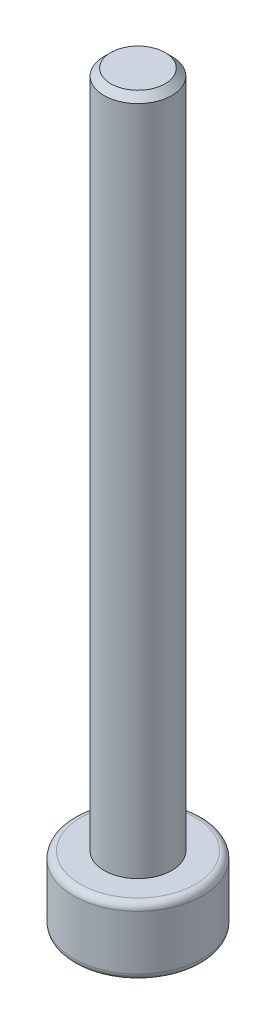
SolidWorks part; units mm, degrees
material "AISI 304"
ref_plane "前视基准面" through (0, 0, 0) normal (0, 0, 1) x (1, 0, 0)
ref_plane "上视基准面" through (0, 0, 0) normal (0, 1, 0) x (1, 0, 0)
ref_plane "右视基准面" through (0, 0, 0) normal (1, 0, 0) x (0, 0, -1)
sketch "草图1" plane through (0, 0, 0) normal (0, 1, 0) x (1, 0, 0)
  circle A0 centre (0, 0) radius 2.85
  dimension "D1" = 5.7
extrude "凸台-拉伸1" add sketch "草图1" along normal blind 3
sketch "草图2" plane through (0, 3, 0) normal (0, 1, 0) x (1, 0, 0)
  circle A0 centre (0, 0) radius 1.5
  dimension "D1" = 3
extrude "凸台-拉伸2" add sketch "草图2" along normal blind 30
sketch "草图3" plane through (0, 0, 0) normal (0, -1, 0) x (1, 0, 0)
  circle A0 centre (0, 0) radius 1.29
  dimension "D1" = 2.58
extrude "切除-拉伸1" cut sketch "草图3" against normal blind 1.3
fillet "圆角1" radius 0.3 2 edges at (0, 3, 2.85) (0, 0, 2.85)
chamfer "倒角1" distance 0.3 angle 45 1 edges at (0, 33, 1.5)
chamfer "倒角2" distance 0.15 angle 45 1 edges at (0, 0, -1.29)
